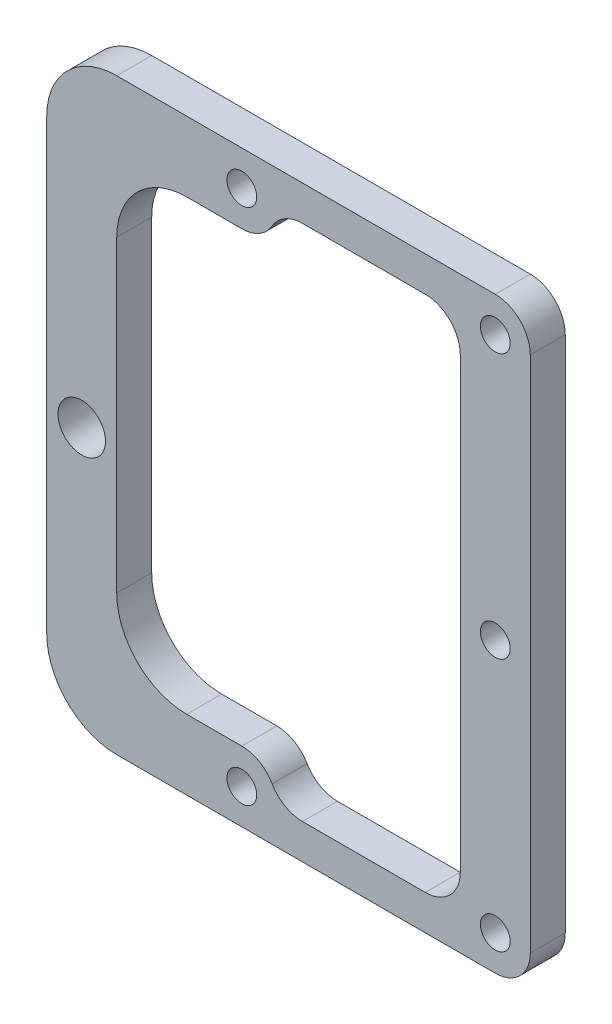
SolidWorks part; units mm, degrees
material "ABS PC"
ref_plane "Front Plane" through (0, 0, 0) normal (0, 0, 1) x (1, 0, 0)
ref_plane "Top Plane" through (0, 0, 0) normal (0, 1, 0) x (1, 0, 0)
ref_plane "Right Plane" through (0, 0, 0) normal (1, 0, 0) x (0, 0, -1)
sketch "Sketch1" plane through (0, 0, 0) normal (0, 0, 1) x (1, 0, 0)
  line L0 (-23, -50.175) -> (0, -50.175)
  line L1 (3.175, -47) -> (3.175, 0)
  line L2 (-23, 3.175) -> (0, 3.175)
  line L3 (-23, -43.825) -> (-34.3483, -43.825)
  line L4 (-23, -50.175) -> (-40.6983, -50.175)
  line L5 (-19.825, 0) -> (-3.175, 0)
  line L6 (-3.175, 0) -> (-3.175, -47)
  line L7 (-40.6983, -26.0624) -> (-40.6983, -50.175)
  line L8 (-19.825, -47) -> (-3.175, -47)
  line L9 (-34.3483, -26.0624) -> (-34.3483, -43.825)
  line L10 (-23, 3.175) -> (-40.6983, 3.175)
  line L11 (-40.6983, -26.0624) -> (-40.6983, 3.175)
  line L12 (-34.3483, -26.0624) -> (-34.3483, -3.175)
  line L13 (-34.3483, -3.175) -> (-23, -3.175)
  circle A0 centre (0, 0) radius 3.175
  circle A1 centre (-37.5233, -26.0624) radius 3.175
  circle A2 centre (0, -24) radius 3.175
  circle A3 centre (-23, 0) radius 3.175
  circle A4 centre (-23, -47) radius 3.175
  circle A5 centre (0, -47) radius 3.175
  dimension "D1" = 6.35
  dimension "D2" = 6.35
extrude "Boss-Extrude1" add sketch "Sketch1" along normal blind 3.175
hole_wizard "#6 Clearance Hole1" positions "Sketch2" profile "Sketch3" hole size "#6" standard "ANSI Inch" end condition through all
sketch "Sketch2" plane through (0, 0, 3.175) normal (0, 0, 1) x (1, 0, 0)
  point P0 (-37.5233, -26.0624)
  point P4 (-37.5233, -26.0624)
sketch "Sketch3" plane through (-37.5233, -26.0624, 3.175) normal (1, 0, 0) x (0, -1, 0)
  line L0 (0, 0) -> (0, 3.175)
  line L1 (0, 3.175) -> (2.1526, 3.175)
  line L2 (2.1526, 3.175) -> (2.1526, 0)
  line L5 (2.1526, 0) -> (0, 0)
  line L11 (0, -6.35) -> (0, 107.95) construction
  dimension "Thru Hole Dia." = 4.3053
  dimension "Thru Hole Depth" = 3.175
hole_wizard "#2 Clearance Hole1" positions "Sketch4" profile "Sketch5" hole size "#2" standard "ANSI Inch" end condition through all
sketch "Sketch4" plane through (0, 0, 3.175) normal (0, 0, 1) x (1, 0, 0)
  circle A0 centre (0, -24) radius 1.55 construction
  point P0 (-23, -47)
  point P3 (0, -47)
  point P6 (0, 0)
  point P9 (-23, 0)
  point P13 (0, -24)
sketch "Sketch5" plane through (-23, -47, 3.175) normal (1, 0, 0) x (0, -1, 0)
  line L0 (0, 0) -> (0, 3.175)
  line L1 (0, 3.175) -> (1.3525, 3.175)
  line L2 (1.3525, 3.175) -> (1.3525, 0)
  line L5 (1.3525, 0) -> (0, 0)
  line L11 (0, -6.35) -> (0, 107.95) construction
  dimension "Thru Hole Dia." = 2.7051
  dimension "Thru Hole Depth" = 3.175
fillet "Fillet1" radius 3.175 4 edges at (-19.825, 0, 1.5875) (-3.175, 0, 1.5875) (-3.175, -47, 1.5875) (-19.825, -47, 1.5875)
fillet "Fillet2" radius 6.35 4 edges at (-40.6983, 3.175, 1.5875) (-40.6983, -50.175, 1.5875) (-34.3483, -43.825, 1.5875) (-34.3483, -3.175, 1.5875)
